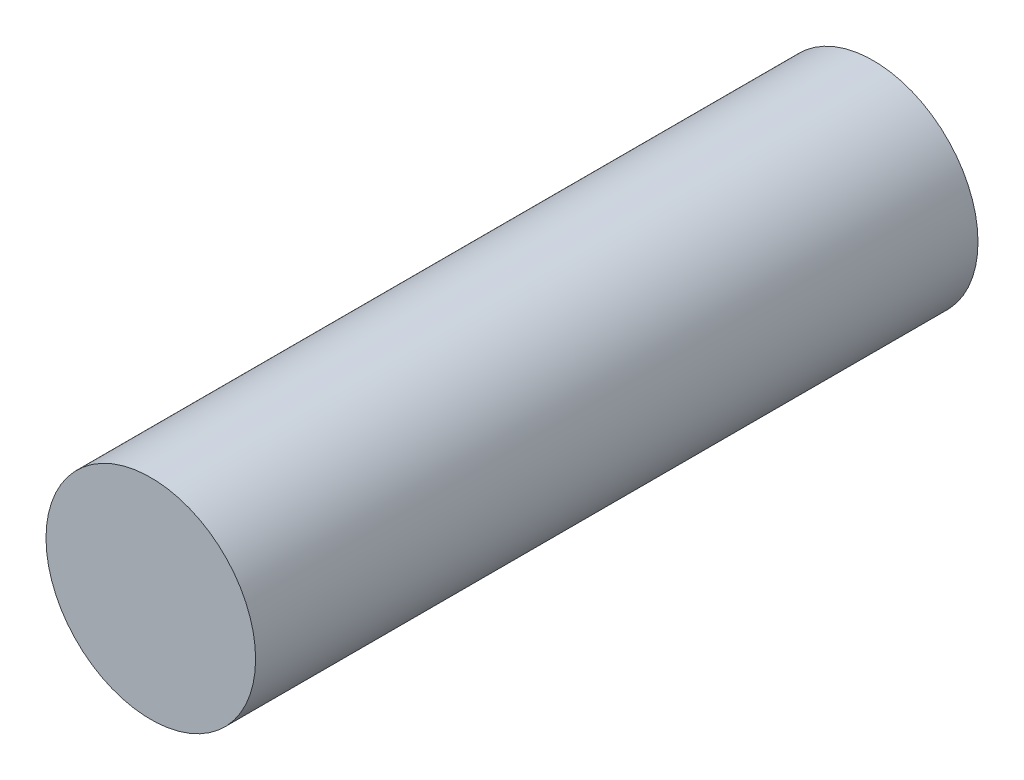
SolidWorks part; units mm, degrees
ref_plane "Front Plane" through (0, 0, 0) normal (0, 0, 1) x (1, 0, 0)
ref_plane "Top Plane" through (0, 0, 0) normal (0, 1, 0) x (1, 0, 0)
ref_plane "Right Plane" through (0, 0, 0) normal (1, 0, 0) x (0, 0, -1)
sketch "Sk_axle" plane through (0, 0, 0) normal (0, 0, 1) x (1, 0, 0)
  circle A0 centre (38.481, -19.05) radius 7.62
extrude "Ext_axle" add sketch "Sk_axle" along normal mid plane 52.5272
